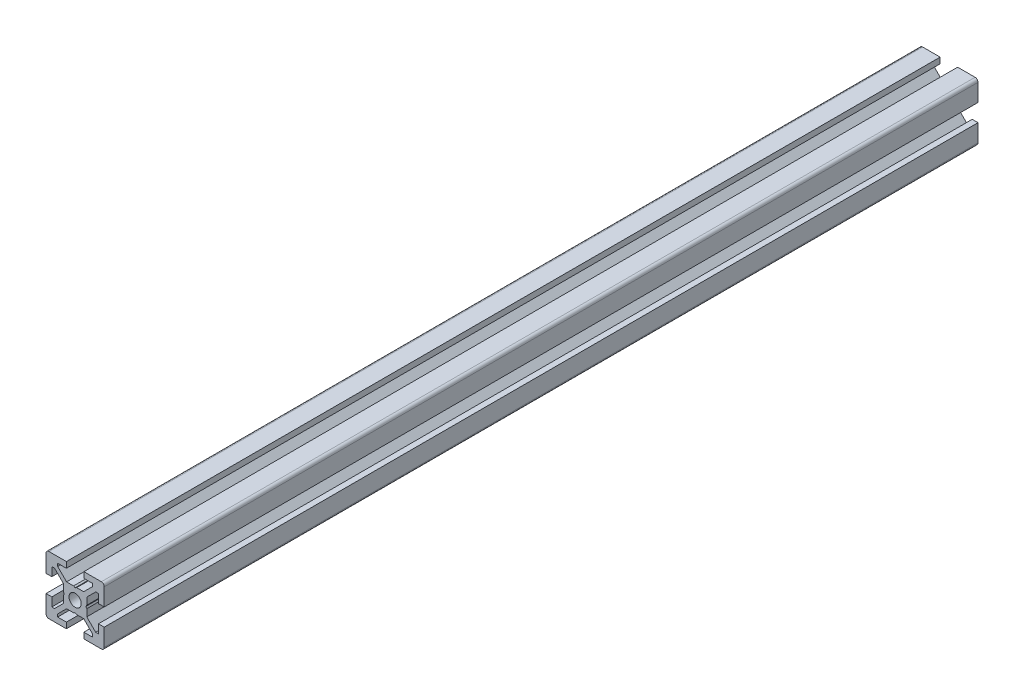
SolidWorks part; units mm, degrees
ref_plane "정면" through (0, 0, 0) normal (0, 0, 1) x (1, 0, 0)
ref_plane "윗면" through (0, 0, 0) normal (0, 1, 0) x (1, 0, 0)
ref_plane "우측면" through (0, 0, 0) normal (1, 0, 0) x (0, 0, -1)
sketch "Model" plane through (0, 0, 0) normal (0, 0, 1) x (1, 0, 0)
  line L0 (-10, 3) -> (-8, 3)
  line L1 (-10, 9) -> (-10, 3)
  line L2 (-3, 10) -> (-9, 10)
  line L3 (-3, 8) -> (-3, 10)
  line L4 (-6, 8) -> (-3, 8)
  line L5 (-6, 7.0607) -> (-6, 8)
  line L6 (-2.9393, 4) -> (-6, 7.0607)
  line L7 (-0.5196, 4) -> (-2.9393, 4)
  line L8 (0, 3.7) -> (-0.5196, 4)
  line L9 (0.5196, 4) -> (0, 3.7)
  line L10 (2.9393, 4) -> (0.5196, 4)
  line L11 (6, 7.0607) -> (2.9393, 4)
  line L12 (6, 8) -> (6, 7.0607)
  line L13 (3, 8) -> (6, 8)
  line L14 (3, 10) -> (3, 8)
  line L15 (9, 10) -> (3, 10)
  line L16 (10, 3) -> (10, 9)
  line L17 (8, 3) -> (10, 3)
  line L18 (8, 6) -> (8, 3)
  line L19 (7.0607, 6) -> (8, 6)
  line L20 (4, 2.9393) -> (7.0607, 6)
  line L21 (4, 0.5196) -> (4, 2.9393)
  line L22 (3.7, 0) -> (4, 0.5196)
  line L23 (4, -0.5196) -> (3.7, 0)
  line L24 (4, -2.9393) -> (4, -0.5196)
  line L25 (7.0607, -6) -> (4, -2.9393)
  line L26 (8, -6) -> (7.0607, -6)
  line L27 (8, -3) -> (8, -6)
  line L28 (10, -3) -> (8, -3)
  line L29 (10, -9) -> (10, -3)
  line L30 (3, -10) -> (9, -10)
  line L31 (3, -8) -> (3, -10)
  line L32 (6, -8) -> (3, -8)
  line L33 (6, -7.0607) -> (6, -8)
  line L34 (2.9393, -4) -> (6, -7.0607)
  line L35 (0.5196, -4) -> (2.9393, -4)
  line L36 (0, -3.7) -> (0.5196, -4)
  line L37 (-0.5196, -4) -> (0, -3.7)
  line L38 (-2.9393, -4) -> (-0.5196, -4)
  line L39 (-6, -7.0607) -> (-2.9393, -4)
  line L40 (-6, -8) -> (-6, -7.0607)
  line L41 (-3, -8) -> (-6, -8)
  line L42 (-3, -10) -> (-3, -8)
  line L43 (-9, -10) -> (-3, -10)
  line L44 (-10, -3) -> (-10, -9)
  line L45 (-8, -3) -> (-10, -3)
  line L46 (-8, -6) -> (-8, -3)
  line L47 (-7.0607, -6) -> (-8, -6)
  line L48 (-4, -2.9393) -> (-7.0607, -6)
  line L49 (-4, -0.5196) -> (-4, -2.9393)
  line L50 (-3.7, 0) -> (-4, -0.5196)
  line L51 (-4, 0.5196) -> (-3.7, 0)
  line L52 (-4, 2.9393) -> (-4, 0.5196)
  line L53 (-7.0607, 6) -> (-4, 2.9393)
  line L54 (-8, 6) -> (-7.0607, 6)
  line L55 (-8, 3) -> (-8, 6)
  arc A0 (-9, 10) -> (-10, 9) centre (-9, 9) ccw
  arc A1 (10, 9) -> (9, 10) centre (9, 9) ccw
  arc A2 (9, -10) -> (10, -9) centre (9, -9) ccw
  arc A3 (-10, -9) -> (-9, -10) centre (-9, -9) ccw
  circle A4 centre (0, 0) radius 2.1
  point P66 (0, 0)
  dimension "D1" = 4.2
extrude "보스-돌출1" add sketch "Model" along normal blind 300
